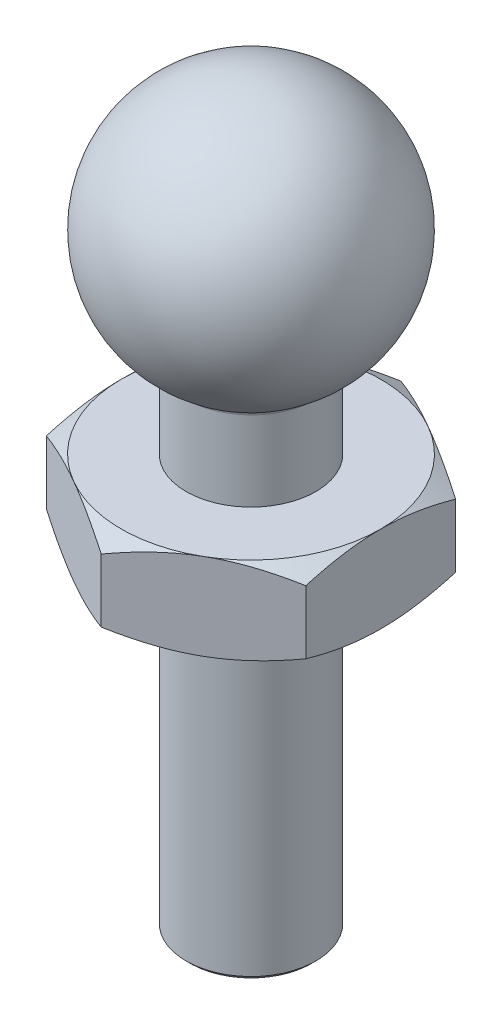
SolidWorks part; units mm, degrees
ref_plane "Front Plane" through (0, 0, 0) normal (0, 0, 1) x (1, 0, 0)
ref_plane "Top Plane" through (0, 0, 0) normal (0, 1, 0) x (1, 0, 0)
ref_plane "Right Plane" through (0, 0, 0) normal (1, 0, 0) x (0, 0, -1)
sketch "Sketch1" plane through (0, 0, 0) normal (0, 0, 1) x (1, 0, 0)
  line L0 (0, 11) -> (0, 0)
  line L1 (0, 0) -> (1.5, 0)
  line L2 (1.5, 0) -> (1.5, 11.4019)
  line L3 (0, 17) -> (0, 11)
  circle A0 centre (0, 14) radius 3 construction
  arc A1 (0, 17) -> (0, 11) centre (0, 14) cw
  dimension "D1" = 6
  dimension "D2" = 1.5
  dimension "D3" = 11
revolve "Revolve1" add sketch "Sketch1" angle 360 about L0
sketch "Sketch2" plane through (0, 0, 0) normal (0, 0, 1) x (1, 0, 0)
  line L0 (-5.2953, 7.5) -> (5.2953, 7.5)
  point P2 (0, 7.5)
  dimension "D1" = 7.5
split line "Split Line1"
chamfer "Chamfer1" distance 0.1 angle 45 1 edges at (-1.5, 0, 0)
ref_plane "Plane1" through (0, 7.5, 0) normal (0, 1, 0) x (1, 0, 0)
sketch "Sketch4" plane through (0, 7.5, 0) normal (0, 1, 0) x (1, 0, 0)
  line L1 (0, 3.4641) -> (-3, 1.7321)
  line L2 (-3, 1.7321) -> (-3, -1.7321)
  line L3 (-3, -1.7321) -> (0, -3.4641)
  line L4 (0, -3.4641) -> (3, -1.7321)
  line L5 (3, -1.7321) -> (3, 1.7321)
  line L6 (3, 1.7321) -> (0, 3.4641)
  circle A0 centre (0, 0) radius 1.5
  circle A1 centre (0, 0) radius 3 construction
  circle A2 centre (0, 0) radius 1.5 construction
  dimension "D1" = 6
extrude "Boss-Extrude1" add sketch "Sketch4" along normal blind 2 separate body
sketch "Sketch5" plane through (0, 7.5, 0) normal (0, -1, 0) x (1, 0, 0)
  circle A0 centre (0, 0) radius 3 construction
  circle A1 centre (0, 0) radius 3
extrude "Cut-Extrude7" cut sketch "Sketch5" against normal blind 2 draft 60 flip side to cut
sketch "Sketch6" plane through (0, 9.5, 0) normal (0, 1, 0) x (1, 0, 0)
  circle A0 centre (0, 0) radius 3 construction
  circle A1 centre (0, 0) radius 3
extrude "Cut-Extrude8" cut sketch "Sketch6" against normal blind 2 draft 60 flip side to cut
fillet "Fillet1" radius 0.1 1 edges at (-1.5, 11.4019, 0)
